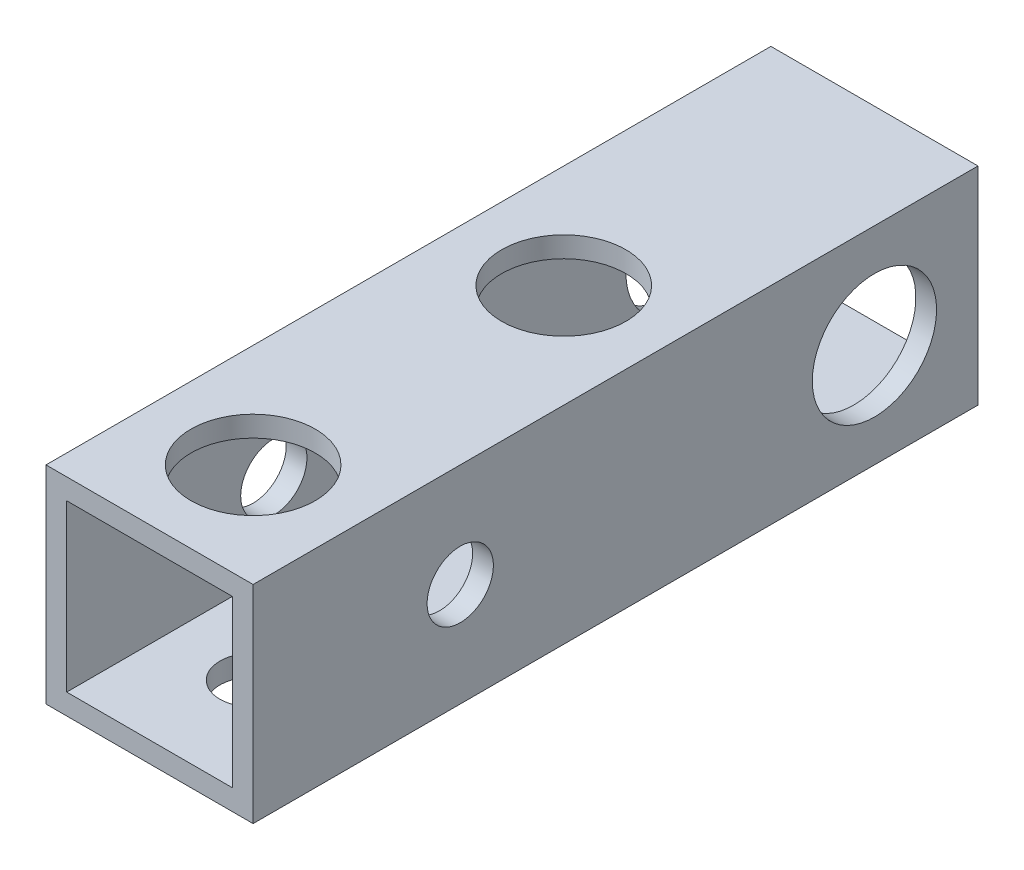
SolidWorks part; units mm, degrees
ref_plane "正面" through (0, 0, 0) normal (0, 0, 1) x (1, 0, 0)
ref_plane "平面" through (0, 0, 0) normal (0, 1, 0) x (1, 0, 0)
ref_plane "右側面" through (0, 0, 0) normal (1, 0, 0) x (0, 0, -1)
sketch "ｽｹｯﾁ1" plane through (0, 0, 0) normal (0, 0, 1) x (1, 0, 0)
  line L5 (-5, -5) -> (5, -5)
  line L6 (-5, -5) -> (-5, 5)
  line L7 (-5, 5) -> (5, 5)
  line L8 (5, -5) -> (5, 5)
  line L9 (-5, -5) -> (5, 5) construction
  line L10 (-5, 5) -> (5, -5) construction
  line L11 (4, -4) -> (-4, -4)
  line L12 (4, -4) -> (4, 4)
  line L13 (4, 4) -> (-4, 4)
  line L14 (-4, -4) -> (-4, 4)
  line L15 (4, -4) -> (-4, 4) construction
  line L16 (4, 4) -> (-4, -4) construction
  point P0 (0, 0)
  point P7 (0, 0)
  dimension "D1" = 10
  dimension "D2" = 10
  dimension "D3" = 8
extrude "ﾎﾞｽ - 押し出し1" add sketch "ｽｹｯﾁ1" along normal blind 80
sketch "ｽｹｯﾁ2" plane through (-5, 0, 0) normal (-1, 0, 0) x (0, 0, 1)
  line L0 (0, 5) -> (0, -5) construction
  line L1 (80, -5) -> (0, -5) construction
  line L2 (80, 5) -> (80, -5) construction
  circle A0 centre (5, 0) radius 3
  circle A1 centre (75, 0) radius 3
  dimension "D1" = 6
  dimension "D2" = 6
  dimension "D3" = 5
  dimension "D4" = 5
  dimension "D5" = 5
  dimension "D6" = 5
extrude "ｶｯﾄ - 押し出し1" cut sketch "ｽｹｯﾁ2" against normal through all
sketch "ｽｹｯﾁ3" plane through (0, 5, 0) normal (0, 1, 0) x (1, 0, 0)
  line L0 (5, -80) -> (-5, -80) construction
  line L1 (5, -80) -> (5, 0) construction
  line L2 (5, 0) -> (-5, 0) construction
  line L3 (-5, -80) -> (-5, 0) construction
  circle A0 centre (0, -65) radius 3
  circle A1 centre (0, -15) radius 3
  dimension "D1" = 6
  dimension "D2" = 15
  dimension "D3" = 5
  dimension "D4" = 6
  dimension "D5" = 15
  dimension "D6" = 5
extrude "ｶｯﾄ - 押し出し2" cut sketch "ｽｹｯﾁ3" against normal blind 10
sketch "ｽｹｯﾁ4" plane through (0, 5, 0) normal (0, 1, 0) x (1, 0, 0)
  line L0 (-5, -80) -> (-5, 0) construction
  circle A0 centre (0, -30) radius 1.6
  circle A1 centre (0, -50) radius 1.6
  circle A2 centre (0, -15) radius 3 construction
  circle A3 centre (0, -65) radius 3 construction
  dimension "D1" = 3.2
  dimension "D2" = 3.2
  dimension "D3" = 15
  dimension "D4" = 15
  dimension "D5" = 5
  dimension "D6" = 5
extrude "ｶｯﾄ - 押し出し3" cut sketch "ｽｹｯﾁ4" against normal blind 10
sketch "ｽｹｯﾁ5" plane through (-5, 0, 0) normal (-1, 0, 0) x (0, 0, 1)
  line L0 (80, -5) -> (0, -5) construction
  line L1 (80, 5) -> (0, 5) construction
  circle A0 centre (25, 0) radius 1.6
  circle A1 centre (55, 0) radius 1.6
  circle A2 centre (5, 0) radius 3 construction
  circle A3 centre (75, 0) radius 3 construction
  dimension "D1" = 3.2
  dimension "D2" = 20
  dimension "D3" = 5
  dimension "D4" = 3.2
  dimension "D5" = 5
  dimension "D6" = 20
extrude "ｶｯﾄ - 押し出し4" cut sketch "ｽｹｯﾁ5" against normal through all
sketch "ｽｹｯﾁ6" plane through (0, 5, 0) normal (0, 1, 0) x (1, 0, 0)
  line L0 (-5, -80) -> (-5, 0) construction
  line L1 (5, -80) -> (-5, -80)
  line L2 (5, -80) -> (5, -35)
  line L3 (5, -35) -> (-5, -35)
  line L4 (-5, -80) -> (-5, -35)
  line L5 (5, 0) -> (-5, 0) construction
  dimension "D1" = 35
extrude "ｶｯﾄ - 押し出し5" cut sketch "ｽｹｯﾁ6" against normal blind 10
sketch "ｽｹｯﾁ7" plane through (0, 5, 0) normal (0, 1, 0) x (1, 0, 0)
  circle A0 centre (0, -30) radius 3
  dimension "D1" = 6
extrude "ｶｯﾄ - 押し出し6" cut sketch "ｽｹｯﾁ7" against normal blind 2
